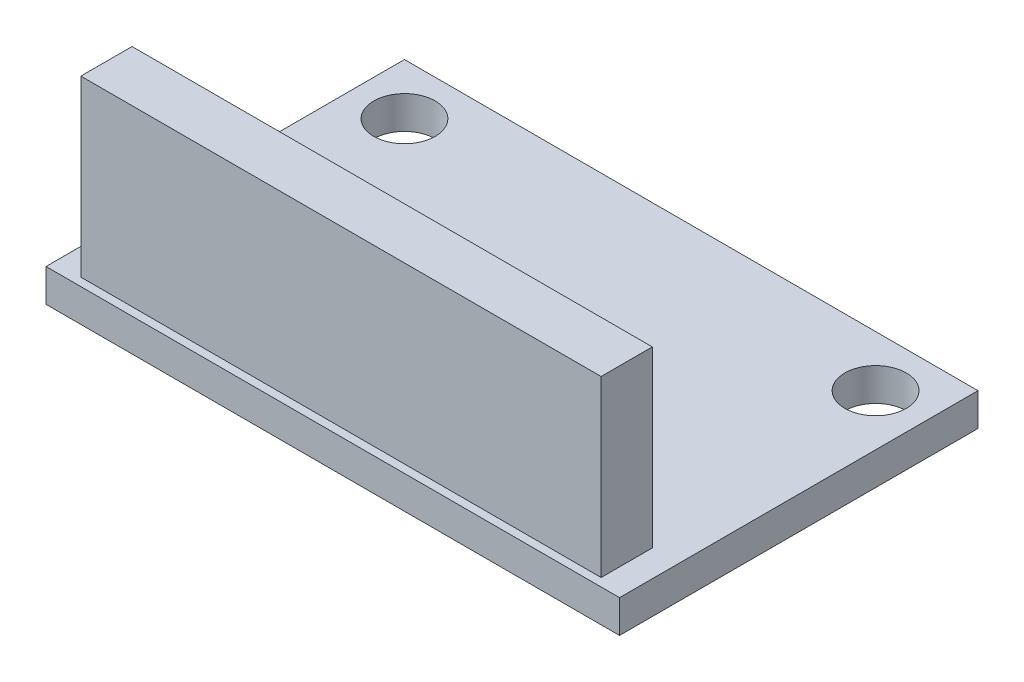
SolidWorks part; units mm, degrees
ref_plane "Front Plane" through (0, 0, 0) normal (0, 0, 1) x (1, 0, 0)
ref_plane "Top Plane" through (0, 0, 0) normal (0, 1, 0) x (1, 0, 0)
ref_plane "Right Plane" through (0, 0, 0) normal (1, 0, 0) x (0, 0, -1)
other "Configuration Table"
sketch "Sketch1" plane through (0, 0, 0) normal (0, 1, 0) x (1, 0, 0)
  line L1 (0, 0) -> (28, 0)
  line L2 (0, 0) -> (0, 17.5)
  line L3 (0, 17.5) -> (28, 17.5)
  line L4 (28, 0) -> (28, 17.5)
extrude "PCB" add sketch "Sketch1" along normal blind 1.6
sketch "Sketch2" plane through (0, 0, 0) normal (0, 1, 0) x (1, 0, 0)
  circle A0 centre (2.5, 15) radius 1.5
extrude "Mount_hole_1" cut sketch "Sketch2" against normal through all and the other way through all
sketch "Sketch3" plane through (0, 0, 0) normal (0, 1, 0) x (1, 0, 0)
  circle A0 centre (25.5, 15) radius 1.5
extrude "Mount_hole_2" cut sketch "Sketch3" against normal through all and the other way through all
sketch "Sketch4" plane through (0, 0, 0) normal (0, 1, 0) x (1, 0, 0)
  line L1 (1.3, 0.4) -> (26.7, 0.4)
  line L2 (1.3, 0.4) -> (1.3, 2.9)
  line L3 (1.3, 2.9) -> (26.7, 2.9)
  line L4 (26.7, 0.4) -> (26.7, 2.9)
extrude "Header_10pin" add sketch "Sketch4" along normal blind 8.5 from offset 1.6
sketch "Sketch5" plane through (0, 0, 0) normal (0, 1, 0) x (1, 0, 0)
  line L1 (11, 6.5) -> (16, 6.5)
  line L2 (11, 6.5) -> (11, 9.5)
  line L3 (11, 9.5) -> (16, 9.5)
  line L4 (16, 6.5) -> (16, 9.5)
extrude "ADS1115_IC" add sketch "Sketch5" along normal blind 1 from offset 1.6
sketch "Sketch6" plane through (0, 0, 0) normal (0, 1, 0) x (1, 0, 0)
  line L1 (17.5, 6.5) -> (19.5, 6.5)
  line L2 (17.5, 6.5) -> (17.5, 7.7)
  line L3 (17.5, 7.7) -> (19.5, 7.7)
  line L4 (19.5, 6.5) -> (19.5, 7.7)
extrude "Caps" add sketch "Sketch6" along normal blind 0.8 from offset 1.6
